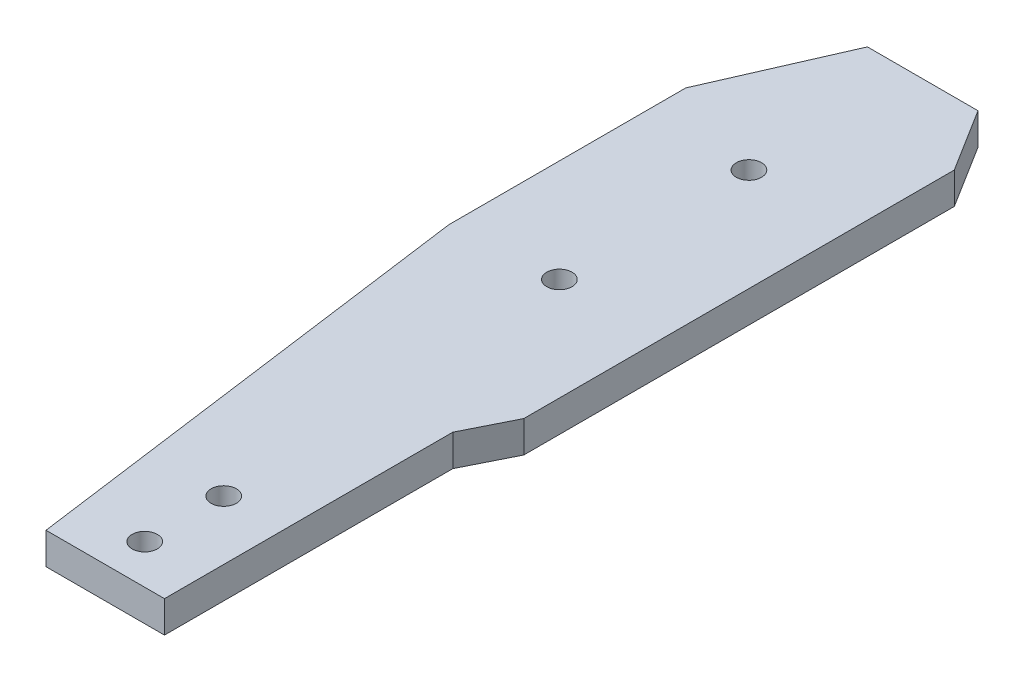
SolidWorks part; units mm, degrees
ref_plane "Front Plane" through (0, 0, 0) normal (0, 0, 1) x (1, 0, 0)
ref_plane "Top Plane" through (0, 0, 0) normal (0, 1, 0) x (1, 0, 0)
ref_plane "Right Plane" through (0, 0, 0) normal (1, 0, 0) x (0, 0, -1)
sketch "Sketch1" plane through (0, 0, 0) normal (0, 1, 0) x (1, 0, 0)
  line L0 (-7, -16) -> (-7, -46)
  line L1 (-7, -46) -> (1, -105)
  line L2 (1, -105) -> (16, -105)
  line L3 (16, -105) -> (16, -68.5)
  line L5 (16, -68.5) -> (19, -62.5)
  line L6 (19, -62.5) -> (19, -8)
  line L7 (19, -8) -> (14, 0)
  line L8 (14, 0) -> (0, 0)
  line L9 (0, 0) -> (-7, -16)
  point P6 (0, 0)
  point P10 (-4.5964, -16.4225)
  point P12 (14, -105)
  point P13 (14, -105)
  point P14 (0, -105)
  dimension "D1" = 30
  dimension "D2" = 16
  dimension "D3" = 14
  dimension "D4" = 8
  dimension "D5" = 5
  dimension "D6" = 105
  dimension "D7" = 6
  dimension "D8" = 15
  dimension "D9" = 36.5
  dimension "D10" = 3
  dimension "D11" = 26
extrude "Boss-Extrude1" add sketch "Sketch1" along normal blind 4
sketch "Sketch2" plane through (0, 4, 0) normal (0, 1, 0) x (1, 0, 0)
  line L0 (19, -62.5) -> (19, -8) construction
  line L1 (14, 0) -> (0, 0) construction
  line L2 (16, -105) -> (16, -68.5) construction
  line L3 (1, -105) -> (16, -105) construction
  circle A0 centre (6, -21) radius 1.6
  circle A1 centre (6, -45) radius 1.6
  circle A2 centre (8.5, -90) radius 1.6
  circle A3 centre (8.5, -100) radius 1.6
  point P16 (0, 0)
  point P17 (0, 0)
  dimension "D1" = 3.2
  dimension "D3" = 21
  dimension "D4" = 3.2
  dimension "D5" = 3.2
  dimension "D6" = 3.2
  dimension "D7" = 24
  dimension "D8" = 7.5
  dimension "D9" = 10
  dimension "D10" = 5
  dimension "D2" = 13
extrude "Cut-Extrude1" cut sketch "Sketch2" against normal blind 4
